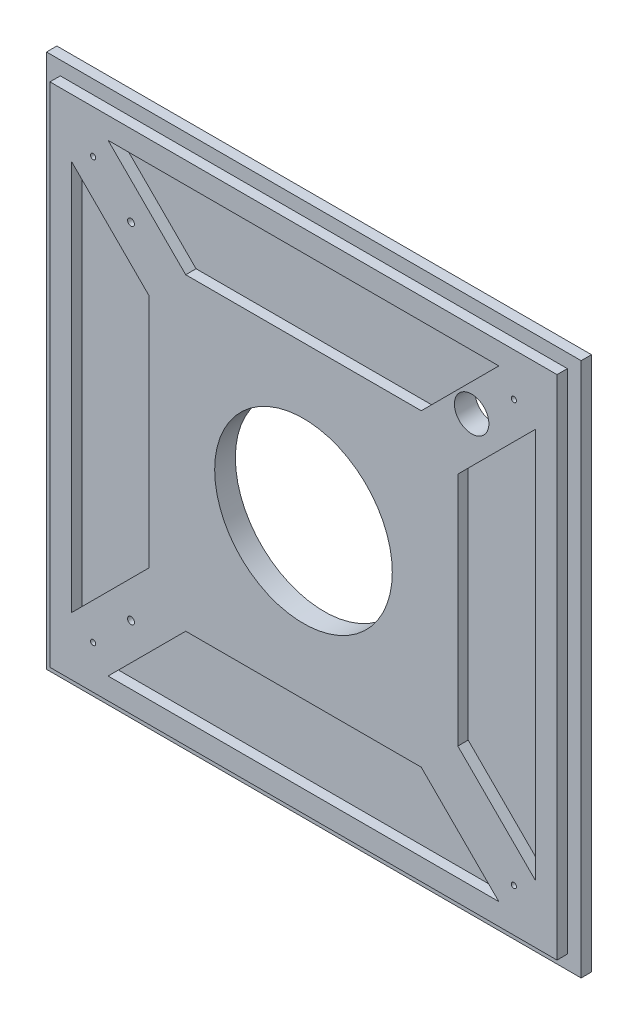
SolidWorks part; units mm, degrees
ref_plane "Front Plane" through (0, 0, 0) normal (0, 0, 1) x (1, 0, 0)
ref_plane "Top Plane" through (0, 0, 0) normal (0, 1, 0) x (1, 0, 0)
ref_plane "Right Plane" through (0, 0, 0) normal (1, 0, 0) x (0, 0, -1)
sketch "Sketch1" plane through (0, 0, 0) normal (0, 0, 1) x (1, 0, 0)
  line L1 (0, 0) -> (310, 0)
  line L2 (0, 0) -> (0, -310)
  line L3 (0, -310) -> (310, -310)
  line L4 (310, 0) -> (310, -310)
  dimension "D1" = 310
  dimension "D2" = 310
extrude "Boss-Extrude1" add sketch "Sketch1" along normal blind 6
sketch "Sketch3" plane through (0, 0, 6) normal (0, 0, 1) x (1, 0, 0)
  line L0 (0, 0) -> (310, -310) construction
  line L1 (302, -8) -> (302, -33)
  line L2 (310, 0) -> (0, -310) construction
  line L3 (302, -8) -> (277, -8)
  line L4 (8, -8) -> (8, -33)
  line L5 (8, -8) -> (33, -8)
  line L6 (8, -302) -> (8, -277)
  line L7 (8, -302) -> (33, -302)
  line L8 (302, -302) -> (277, -302)
  line L9 (302, -302) -> (302, -277)
  line L10 (0, 0) -> (0, -310) construction
  line L11 (268.2868, -20.5) -> (223.2868, -65.5)
  line L13 (20.5, -41.7132) -> (65.5, -86.7132)
  line L15 (41.7132, -289.5) -> (86.7132, -244.5)
  line L17 (289.5, -41.7132) -> (244.5, -86.7132)
  line L19 (33, -8) -> (277, -8)
  line L20 (268.2868, -20.5) -> (41.7132, -20.5)
  line L21 (8, -33) -> (8, -277)
  line L22 (20.5, -41.7132) -> (20.5, -268.2868)
  line L23 (302, -33) -> (302, -277)
  line L24 (289.5, -41.7132) -> (289.5, -268.2868)
  line L25 (33, -302) -> (277, -302)
  line L26 (268.2868, -289.5) -> (41.7132, -289.5)
  line L27 (86.7132, -65.5) -> (223.2868, -65.5)
  line L31 (244.5, -86.7132) -> (244.5, -223.2868)
  line L33 (86.7132, -244.5) -> (223.2868, -244.5)
  line L35 (65.5, -86.7132) -> (65.5, -223.2868)
  line L36 (86.7132, -65.5) -> (41.7132, -20.5)
  line L39 (244.5, -223.2868) -> (289.5, -268.2868)
  line L40 (223.2868, -244.5) -> (268.2868, -289.5)
  line L42 (65.5, -223.2868) -> (20.5, -268.2868)
  line L44 (310, 0) -> (0, 0) construction
  line L45 (310, -310) -> (310, 0) construction
  line L46 (0, -310) -> (310, -310) construction
  point P4 (135, -155)
  point P9 (175, -155)
  point P10 (155, -135)
  point P11 (155, -175)
  point P13 (155, -155)
  dimension "D1" = 25
  dimension "D2" = 25
  dimension "D3" = 25
  dimension "D4" = 25
  dimension "D5" = 25
  dimension "D6" = 25
  dimension "D7" = 25
  dimension "D8" = 25
  dimension "D9" = 8
  dimension "D10" = 45
  dimension "D11" = 12.5
  dimension "D12" = 12.5
  dimension "D13" = 12.5
  dimension "D14" = 12.5
  dimension "D15" = 20
  dimension "D16" = 20
  dimension "D17" = 20
  dimension "D18" = 20
  dimension "D19" = 45
  dimension "D20" = 45
  dimension "D21" = 45
  dimension "D22" = 15
  dimension "D23" = 15
  dimension "D24" = 15
  dimension "D25" = 15
  dimension "D26" = 15
  dimension "D27" = 15
  dimension "D28" = 15
  dimension "D29" = 15
  dimension "D30" = 8
  dimension "D31" = 8
  dimension "D32" = 8
extrude "Boss-Extrude2" add sketch "Sketch3" along normal blind 6
sketch "Sketch4" plane through (0, 0, 12) normal (0, 0, 1) x (1, 0, 0)
  line L0 (0, 0) -> (310, -310) construction
  line L1 (310, 0) -> (0, -310) construction
  circle A0 centre (155, -155) radius 51.5
  dimension "D1" = 103
extrude "Cut-Extrude1" cut sketch "Sketch4" against normal through all
sketch "Sketch10" plane through (0, 0, 0) normal (0, 0, -1) x (-1, 0, 0)
  line L0 (-310, -52.5) -> (0, -52.5)
  line L1 (-310, -310) -> (-310, 0) construction
  line L2 (0, 0) -> (0, -310) construction
  line L3 (-252.5, 0) -> (-252.5, -310)
  line L4 (-310, 0) -> (0, 0) construction
  line L5 (0, -310) -> (-310, -310) construction
  circle A0 centre (-252.5, -52.5) radius 10
  dimension "D3" = 20
  dimension "D1" = 57.5
  dimension "D2" = 52.5
extrude "corner cord hole" cut sketch "Sketch10" against normal through all contours A0
sketch "Sketch11" plane through (0, 0, 0) normal (0, 0, -1) x (-1, 0, 0)
  line L0 (-255, -55) -> (-55, -55) construction
  line L5 (-55, -55) -> (-55, -255) construction
  line L6 (-55, -255) -> (-255, -255) construction
  line L7 (-255, -255) -> (-255, -55) construction
  line L8 (-155, -103.5) -> (-155, -206.5) construction
  line L9 (-206.5, -155) -> (-103.5, -155) construction
  circle A0 centre (-155, -155) radius 51.5 construction
  circle A2 centre (-55, -55) radius 2
  circle A3 centre (-55, -255) radius 2
  point P11 (-155, -155)
  dimension "D6" = 4
  dimension "D7" = 4
  dimension "D1" = 200
  dimension "D2" = 200
  dimension "D3" = 100
  dimension "D4" = 100
extrude "Cut-Extrude5" cut sketch "Sketch11" against normal through all
sketch "Sketch12" plane through (0, 0, 0) normal (0, 0, -1) x (-1, 0, 0)
  line L0 (-339.9534, -155) -> (14.9572, -155) construction
  line L1 (-155, 5.3762) -> (-155, -332.8718) construction
  line L2 (0, 0) -> (0, -310) construction
  line L3 (-310, -310) -> (-310, 0) construction
  line L4 (-310, 0) -> (0, 0) construction
  line L5 (0, -310) -> (-310, -310) construction
  line L6 (-260, -155) -> (-260, -260) construction
  line L7 (-260, -260) -> (-50, -260) construction
  line L8 (-50, -260) -> (-50, -50) construction
  line L9 (-50, -50) -> (-260, -50) construction
  line L10 (-260, -50) -> (-260, -155) construction
  line L11 (-260, -110) -> (-285, -110) construction
  line L12 (-285, -110) -> (-285, -200) construction
  line L13 (-285, -200) -> (-260, -200) construction
  line L15 (-260, -99) -> (-285, -99)
  line L16 (-260, -99) -> (-260, -109)
  line L17 (-260, -109) -> (-285, -109)
  line L18 (-285, -99) -> (-285, -109)
  line L19 (-260, -211) -> (-285, -211)
  line L20 (-260, -211) -> (-260, -201)
  line L21 (-260, -201) -> (-285, -201)
  line L22 (-285, -211) -> (-285, -201)
  dimension "D1" = 105
  dimension "D2" = 105
  dimension "D3" = 210
  dimension "D4" = 210
  dimension "D5" = 25
  dimension "D6" = 105
  dimension "D7" = 90
  dimension "D8" = 60
  dimension "D9" = 1
  dimension "D10" = 1
  dimension "D11" = 10
  dimension "D12" = 10
  dimension "D13" = 25
  dimension "D14" = 25
extrude "Boss-Extrude3" add sketch "Sketch12" along normal blind 6.5
sketch "Sketch13" plane through (0, 0, -6.5) normal (0, 0, -1) x (-1, 0, 0)
  line L1 (-285, -99) -> (-260, -99)
  line L2 (-285, -99) -> (-285, -211)
  line L3 (-285, -211) -> (-260, -211)
  line L4 (-260, -99) -> (-260, -211)
extrude "Boss-Extrude4" add sketch "Sketch13" along normal blind 8
sketch "Sketch14" plane through (0, 0, 12) normal (0, 0, 1) x (1, 0, 0)
  line L0 (310, 0) -> (0, 0) construction
  line L1 (28, -28) -> (282, -28)
  line L2 (28, -28) -> (28, -282)
  line L3 (28, -282) -> (282, -282)
  line L4 (282, -28) -> (282, -282)
  line L6 (310, -310) -> (310, 0) construction
  circle A0 centre (33, -33) radius 1.5
  circle A1 centre (277, -33) radius 1.5
  circle A3 centre (277, -277) radius 1.5
  circle A4 centre (33, -277) radius 1.5
  point P19 (16.877, -258.3473)
  dimension "D5" = 3
  dimension "D8" = 3
  dimension "D11" = 3
  dimension "D14" = 3
  dimension "D1" = 254
  dimension "D2" = 254
  dimension "D3" = 28
  dimension "D4" = 28
  dimension "D6" = 5
  dimension "D7" = 5
  dimension "D9" = 5
  dimension "D10" = 5
  dimension "D12" = 5
  dimension "D13" = 5
  dimension "D15" = 5
  dimension "D16" = 5
extrude "Cut-Extrude6" cut sketch "Sketch14" against normal through all and the other way through all contours A4 | A1 | A0 | A3
